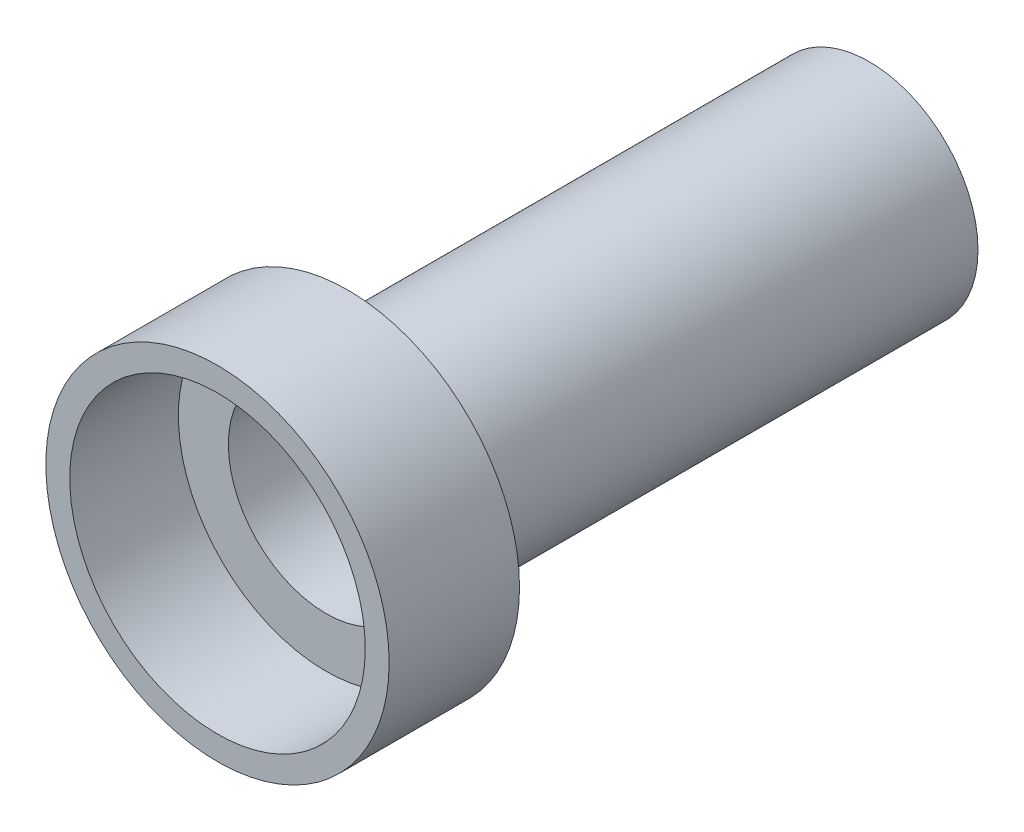
SolidWorks part; units mm, degrees
ref_plane "Plan de face" through (0, 0, 0) normal (0, 0, 1) x (1, 0, 0)
ref_plane "Plan de dessus" through (0, 0, 0) normal (0, 1, 0) x (1, 0, 0)
ref_plane "Plan de droite" through (0, 0, 0) normal (1, 0, 0) x (0, 0, -1)
sketch "Esquisse1" plane through (0, 0, 0) normal (0, 0, 1) x (1, 0, 0)
  circle A0 centre (0, 0) radius 1.975
extrude "Boss.-Extru.1" add sketch "Esquisse1" along normal blind 1.5
sketch "Esquisse2" plane through (0, 0, 0) normal (0, 0, -1) x (-1, 0, 0)
  circle A0 centre (0, 0) radius 1.25
extrude "Boss.-Extru.2" add sketch "Esquisse2" along normal blind 6
sketch "Esquisse3" plane through (0, 0, 1.5) normal (0, 0, 1) x (1, 0, 0)
  circle A0 centre (0, 0) radius 1.7
extrude "Enlèv. mat.-Extru.2" cut sketch "Esquisse3" against normal blind 1.25
sketch "Esquisse4" plane through (0, 0, -6) normal (0, 0, -1) x (-1, 0, 0)
  circle A0 centre (0, 0) radius 1.125
  point P3 (2.8097, -0.8082)
extrude "Enlèv. mat.-Extru.4" cut sketch "Esquisse4" against normal blind 51.25
